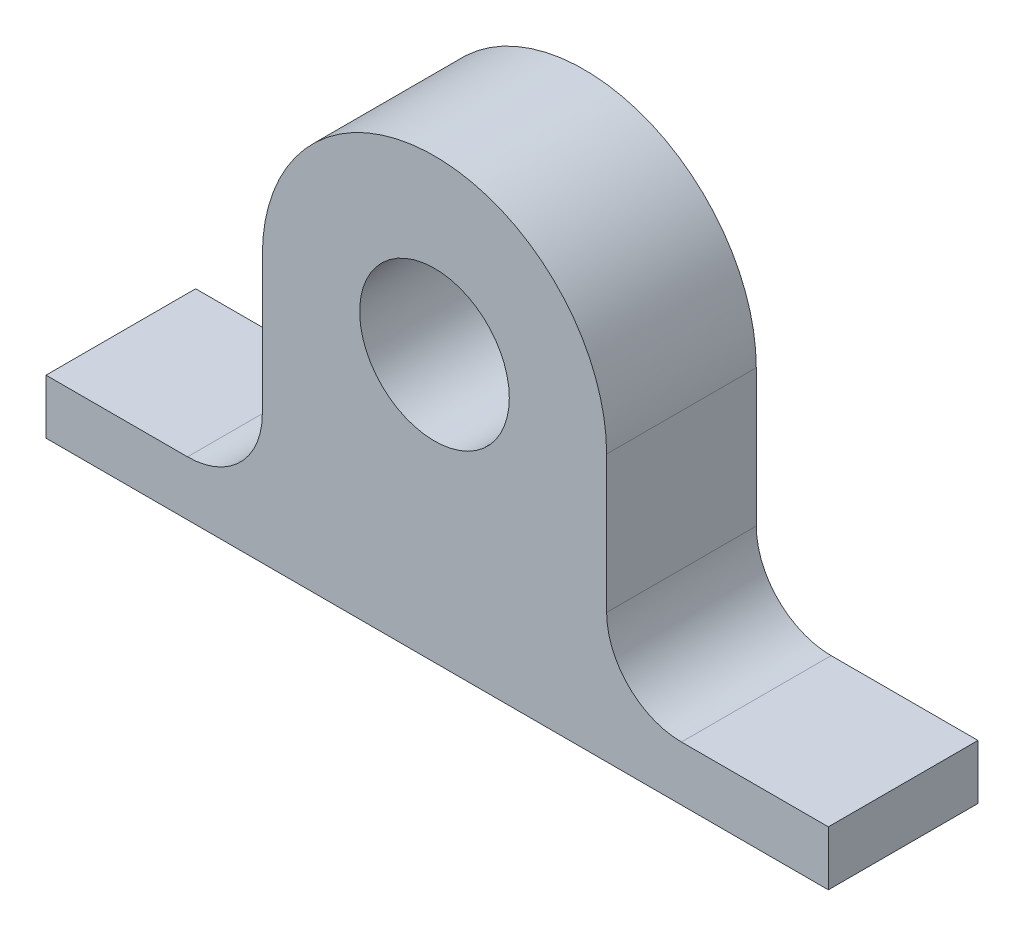
SolidWorks part; units mm, degrees
ref_plane "Front Plane" through (0, 0, 0) normal (0, 0, 1) x (1, 0, 0)
ref_plane "Top Plane" through (0, 0, 0) normal (0, 1, 0) x (1, 0, 0)
ref_plane "Right Plane" through (0, 0, 0) normal (1, 0, 0) x (0, 0, -1)
sketch "Sketch1" plane through (0, 0, 0) normal (0, 0, 1) x (1, 0, 0)
  line L0 (-20.7673, 0) -> (-20.7673, 2.9186)
  line L2 (0, 21.755) -> (0, -18.7365) construction
  line L3 (-20.7673, 0) -> (21.0556, 0)
  line L5 (21.0556, 0) -> (21.0556, 2.9186)
  line L7 (-20.7673, 2.9186) -> (-13.2026, 2.9186)
  line L8 (-9.2026, 6.9186) -> (-9.2026, 14.25)
  line L9 (21.0556, 2.9186) -> (13.2026, 2.9186)
  line L10 (9.2026, 6.9186) -> (9.2026, 14.25)
  arc A0 (-9.2026, 14.25) -> (9.2026, 14.25) centre (0, 14.25) cw
  circle A1 centre (0, 14.25) radius 4
  arc A2 (-9.2026, 6.9186) -> (-13.2026, 2.9186) centre (-13.2026, 6.9186) cw
  arc A3 (13.2026, 2.9186) -> (9.2026, 6.9186) centre (13.2026, 6.9186) cw
  dimension "D1" = 8
  dimension "D3" = 4
  dimension "D2" = 14.25
extrude "Boss-Extrude1" add sketch "Sketch1" along normal blind 8
